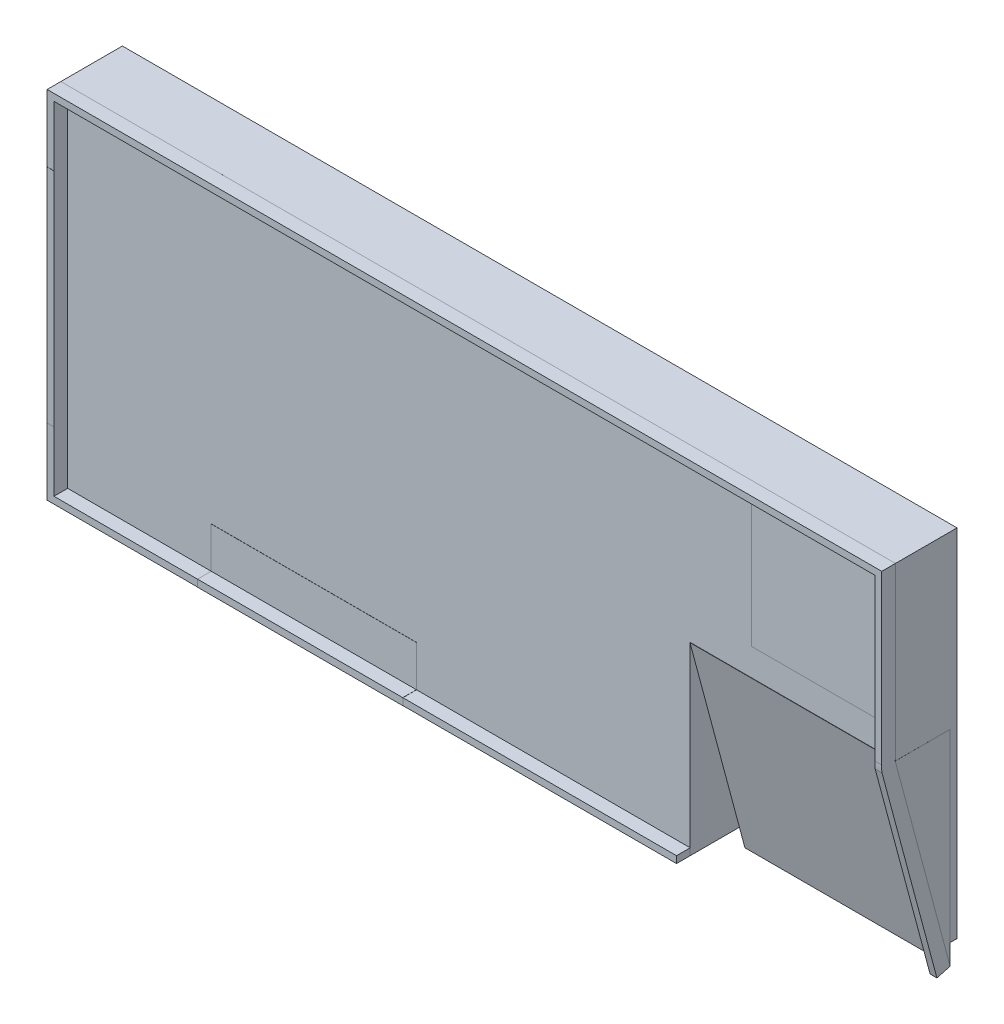
SolidWorks part; units mm, degrees
ref_plane "Front Plane" through (0, 0, 0) normal (0, 0, 1) x (1, 0, 0)
ref_plane "Top Plane" through (0, 0, 0) normal (0, 1, 0) x (1, 0, 0)
ref_plane "Right Plane" through (0, 0, 0) normal (1, 0, 0) x (0, 0, -1)
sketch "Sketch1" plane through (0, 0, 0) normal (0, 0, 1) x (1, 0, 0)
  line L2 (-2312.6035, 1536.6276) -> (3787.3965, 1536.6276)
  line L3 (-2312.6035, 1536.6276) -> (-2312.6035, -1063.3724)
  line L4 (-2312.6035, -1063.3724) -> (3787.3965, -1063.3724)
  line L5 (3787.3965, 1536.6276) -> (3787.3965, -1063.3724)
  dimension "D1" = 6100
  dimension "D2" = 2600
extrude "Boss-Extrude1" add sketch "Sketch1" along normal blind 450
sketch "Sketch4" plane through (3787.3965, 0, 0) normal (1, 0, 0) x (0, 0, -1)
  line L0 (-450, -1063.3724) -> (-450, 1536.6276) construction
  line L1 (-450, 286.6276) -> (-50, 286.6276)
  line L2 (-450, 286.6276) -> (-450, -1063.3724)
  line L3 (-450, -1063.3724) -> (-50, -1063.3724)
  line L4 (-50, 286.6276) -> (-50, -1063.3724)
  line L5 (-450, 1536.6276) -> (0, 1536.6276) construction
  dimension "D1" = 1250
  dimension "D2" = 400
extrude "Cut-Extrude1" cut sketch "Sketch4" against normal blind 1500
sketch "Sketch5" plane through (3787.3965, 0, 0) normal (1, 0, 0) x (0, 0, -1)
  line L0 (-451.7952, 286.1475) -> (-50, 286.6276)
  line L1 (-50, 286.6276) -> (-50, -1213.3724)
  line L2 (-50, -1213.3724) -> (-451.7952, 286.1475)
  dimension "D1" = 1500
  dimension "D2" = 15
extrude "Boss-Extrude3" add sketch "Sketch5" against normal blind 1500
sketch "Sketch6" plane through (0, -93.7805, 349.9938) normal (0, -0.2588, 0.9659) x (1, 0, 0)
  line L0 (3787.3965, 393.3305) -> (3787.3965, -1159.0868) construction
  line L5 (3787.3955, 393.3301) -> (3737.3955, 393.3301)
  line L10 (3787.3955, 393.3301) -> (3787.3955, -1159.0869)
  line L11 (3787.3955, -1159.0869) -> (3737.3955, -1159.0869)
  line L12 (3737.3955, 393.3301) -> (3737.3955, -1159.0869)
  dimension "D1" = 50
  dimension "D2" = 0.001
extrude "Boss-Extrude4" add sketch "Sketch6" along normal blind 100
sketch "Sketch7" plane through (0, 0, 450) normal (0, 0, 1) x (1, 0, 0)
  line L0 (3787.3955, 309.5326) -> (3787.3955, 1536.6266)
  line L1 (3787.3955, 1536.6266) -> (-2312.6025, 1536.6266)
  line L2 (-2312.6025, 1536.6266) -> (-2312.6025, -1063.3714)
  line L3 (-2312.6025, -1063.3714) -> (2287.3955, -1063.3714)
  line L4 (3787.3965, 286.6276) -> (3787.3965, 1536.6276) construction
  line L5 (3787.3965, 1536.6276) -> (-2312.6035, 1536.6276) construction
  line L6 (-2312.6035, 1536.6276) -> (-2312.6035, -1063.3724) construction
  line L7 (-2312.6035, -1063.3724) -> (2287.3965, -1063.3724) construction
  line L8 (3737.3955, 309.5326) -> (3737.3955, 1486.6266)
  line L9 (3737.3955, 1486.6266) -> (-2262.6025, 1486.6266)
  line L10 (-2262.6025, 1486.6266) -> (-2262.6025, -1013.3714)
  line L11 (-2262.6025, -1013.3714) -> (2287.3955, -1013.3714)
  line L12 (2287.3955, -1013.3714) -> (2287.3955, -1063.3714)
  line L13 (3737.3955, 309.5326) -> (3787.3955, 309.5326)
  line L14 (2287.3965, 279.4478) -> (2287.3965, -1063.3724) construction
  dimension "D1" = 0.001
  dimension "D2" = 0.001
  dimension "D3" = 0.001
  dimension "D4" = 0.001
  dimension "D6" = 0.001
  dimension "D5" = 50
extrude "Boss-Extrude5" add sketch "Sketch7" along normal blind 100
sketch "Sketch8" plane through (0, 0, 450) normal (0, 0, 1) x (1, 0, 0)
  line L0 (-2262.6025, 1486.6266) -> (3737.3955, 1486.6266) construction
  line L1 (2737.3945, 1486.6256) -> (3737.3945, 1486.6256)
  line L2 (2737.3945, 1486.6256) -> (2737.3945, 486.6256)
  line L3 (2737.3945, 486.6256) -> (3737.3945, 486.6256)
  line L4 (3737.3945, 1486.6256) -> (3737.3945, 486.6256)
  line L5 (3737.3955, 1486.6266) -> (3737.3955, 309.5326) construction
  dimension "D1" = 1000
  dimension "D2" = 1000
  dimension "D3" = 0.001
  dimension "D4" = 0.001
extrude "Boss-Extrude6" add sketch "Sketch8" along normal blind 1
sketch "Sketch9" plane through (0, 0, 450) normal (0, 0, 1) x (1, 0, 0)
  line L0 (2287.3955, -1013.3714) -> (-2262.6025, -1013.3714) construction
  line L1 (-1212.6035, -713.3704) -> (287.3965, -713.3704)
  line L2 (-1212.6035, -713.3704) -> (-1212.6035, -1013.3704)
  line L3 (-1212.6035, -1013.3704) -> (287.3965, -1013.3704)
  line L4 (287.3965, -713.3704) -> (287.3965, -1013.3704)
  line L5 (2287.3965, 279.4478) -> (2287.3965, -1063.3724) construction
  dimension "D1" = 1500
  dimension "D2" = 300
  dimension "D3" = 2000
  dimension "0" = 0.001
extrude "Boss-Extrude7" add sketch "Sketch9" along normal blind 1
sketch "Sketch11" plane through (0, 0, 550) normal (0, 0, 1) x (1, 0, 0)
  line L0 (-2312.6025, 1536.6266) -> (-2312.6025, -1063.3714) construction
  line L1 (-2312.6025, 1046.6286) -> (-2262.6025, 1046.6286)
  line L2 (-2312.6025, 1046.6286) -> (-2312.6025, -573.3714)
  line L3 (-2312.6025, -573.3714) -> (-2262.6025, -573.3714)
  line L4 (-2262.6025, 1046.6286) -> (-2262.6025, -573.3714)
  line L5 (-2262.6025, -1013.3714) -> (-2262.6025, 1486.6266) construction
  line L6 (2287.3955, -1013.3714) -> (-2262.6025, -1013.3714) construction
  dimension "D1" = 1620
  dimension "D2" = 440
extrude "Boss-Extrude8" add sketch "Sketch11" along normal blind 1
sketch "Sketch12" plane through (3787.3955, 0, 0) normal (1, 0, 0) x (0, 0, -1)
  line L0 (-550, 309.5326) -> (-450, 309.5326)
  line L1 (-450, 309.5326) -> (-451.7951, 286.1472)
  line L2 (-451.7951, 286.1472) -> (-548.3877, 260.2653)
  arc A0 (-550, 309.5326) -> (-548.3877, 260.2653) centre (-336.4004, 291.8628) ccw
extrude "Boss-Extrude9" add sketch "Sketch12" against normal blind 50
sketch "Sketch13" plane through (0, -1013.3714, 0) normal (0, 1, 0) x (1, 0, 0)
  line L1 (-1212.6035, -451) -> (287.3965, -451)
  line L2 (-1212.6035, -451) -> (-1212.6035, -551)
  line L3 (-1212.6035, -551) -> (287.3965, -551)
  line L4 (287.3965, -451) -> (287.3965, -551)
  dimension "D1" = 0
  dimension "D2" = 0
  dimension "D3" = 1500
  dimension "D4" = 100
extrude "Boss-Extrude10" add sketch "Sketch13" along normal blind 1
sketch "Sketch14" plane through (0, 0, 550) normal (0, 0, 1) x (1, 0, 0)
  line L1 (-1211.2484, -1013.3714) -> (288.7516, -1013.3714)
  line L2 (-1211.2484, -1013.3714) -> (-1211.2484, -1063.3714)
  line L3 (-1211.2484, -1063.3714) -> (288.7516, -1063.3714)
  line L4 (288.7516, -1013.3714) -> (288.7516, -1063.3714)
  dimension "D1" = 0
  dimension "D2" = 1500
  dimension "D3" = 50
extrude "Boss-Extrude11" add sketch "Sketch14" along normal blind 1
